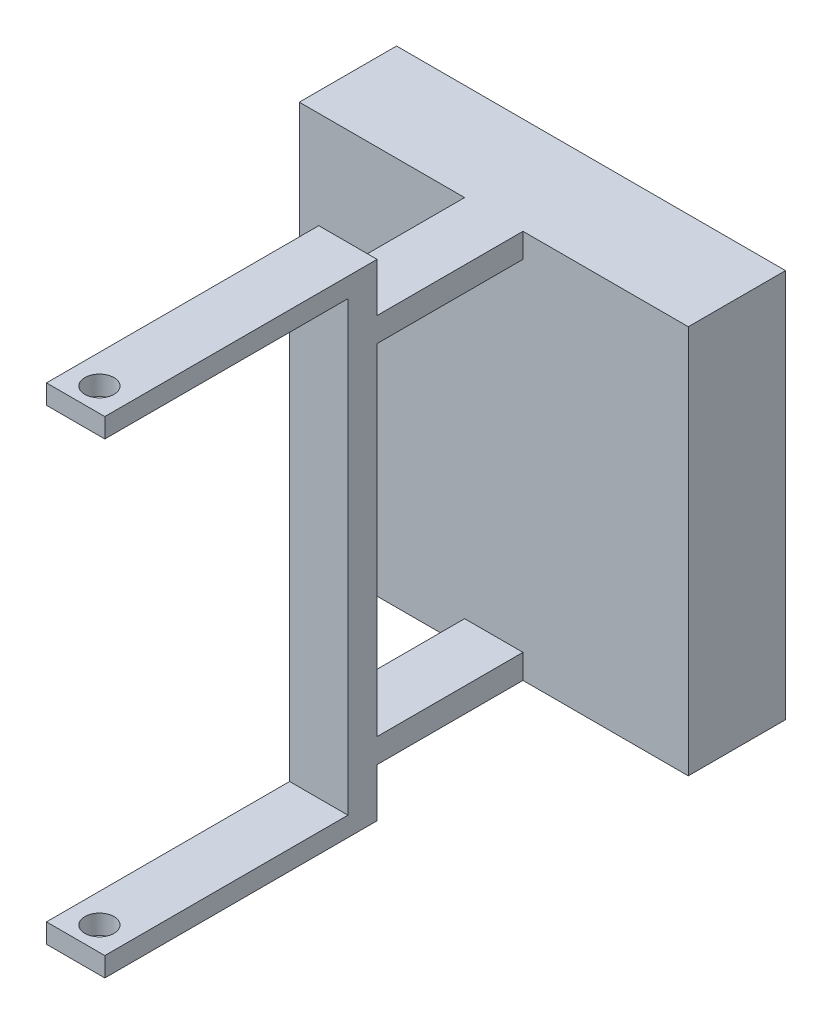
SolidWorks part; units mm, degrees
ref_plane "Front Plane" through (0, 0, 0) normal (0, 0, 1) x (1, 0, 0)
ref_plane "Top Plane" through (0, 0, 0) normal (0, 1, 0) x (1, 0, 0)
ref_plane "Right Plane" through (0, 0, 0) normal (1, 0, 0) x (0, 0, -1)
sketch "Sketch1" plane through (0, 0, 0) normal (0, 0, 1) x (1, 0, 0)
  line L1 (-20, -20) -> (20, -20)
  line L2 (-20, -20) -> (-20, 20)
  line L3 (-20, 20) -> (20, 20)
  line L4 (20, -20) -> (20, 20)
  line L5 (-20, -20) -> (20, 20) construction
  line L6 (-20, 20) -> (20, -20) construction
  point P0 (0, 0)
  dimension "D1" = 40
  dimension "D2" = 40
extrude "Boss-Extrude1" add sketch "Sketch1" along normal blind 10
sketch "Sketch2" plane through (0, 0, 10) normal (0, 0, 1) x (1, 0, 0)
  line L0 (0, -20) -> (3, -20)
  line L1 (-20, -20) -> (20, -20) construction
  line L2 (3, -20) -> (3, -17.5)
  line L3 (3, -17.5) -> (-3, -17.5)
  line L4 (-3, -17.5) -> (-3, -20)
  line L5 (-3, -20) -> (0, -20)
  dimension "D1" = 3
  dimension "D2" = 3
  dimension "D3" = 2.5
extrude "Boss-Extrude2" add sketch "Sketch2" along normal blind 15
mirror "Mirror1" about plane through (0, 0, 0) normal (0, 1, 0) of "Boss-Extrude2"
sketch "Sketch3" plane through (0, 0, 0) normal (0, 0, -1) x (-1, 0, 0)
  line L1 (-6.5, 6.5) -> (6.5, 6.5)
  line L2 (-6.5, 6.5) -> (-6.5, -6.5)
  line L3 (-6.5, -6.5) -> (6.5, -6.5)
  line L4 (6.5, 6.5) -> (6.5, -6.5)
  line L5 (-6.5, 6.5) -> (6.5, -6.5) construction
  line L6 (-6.5, -6.5) -> (6.5, 6.5) construction
  point P0 (0, 0)
  dimension "D1" = 13
  dimension "D2" = 13
ref_plane "Plane4" through (0, 0, 25) normal (0, 0, 1) x (1, 0, 0)
sketch "Sketch6" plane through (0, 0, 25) normal (0, 0, 1) x (1, 0, 0)
  line L1 (-3, 25) -> (3, 25)
  line L2 (-3, 25) -> (-3, -25)
  line L3 (-3, -25) -> (3, -25)
  line L4 (3, 25) -> (3, -25)
  line L5 (-3, 25) -> (3, -25) construction
  line L6 (-3, -25) -> (3, 25) construction
  point P0 (0, 0)
  dimension "D1" = 50
  dimension "D2" = 6
extrude "Boss-Extrude4" add sketch "Sketch6" along normal blind 3
sketch "Sketch7" plane through (0, 0, 28) normal (0, 0, 1) x (1, 0, 0)
  line L0 (3, -25) -> (3, -23)
  line L1 (3, -25) -> (3, 25) construction
  line L2 (3, -23) -> (-3, -23)
  line L3 (-3, 25) -> (-3, -25) construction
  line L4 (-3, -23) -> (-3, -25)
  line L5 (-3, -25) -> (3, -25)
  dimension "D1" = 2
extrude "Boss-Extrude5" add sketch "Sketch7" along normal blind 25
mirror "Mirror2" about plane through (0, 0, 0) normal (0, 1, 0) of "Boss-Extrude5"
sketch "Sketch8" plane through (0, -25, 0) normal (0, -1, 0) x (1, 0, 0)
  circle A0 centre (0, 50.5557) radius 1.5
  dimension "D1" = 3
extrude "Cut-Extrude1" cut sketch "Sketch8" against normal blind 65
sketch "Sketch9" plane through (0, 0, 0) normal (0, 0, -1) x (-1, 0, 0)
  line L0 (-6.5, 6.5) -> (6.5, -6.5) construction
  circle A0 centre (0, 0) radius 10
  dimension "D1" = 20
sketch "Sketch10" plane through (0, 0, 0) normal (0, 0, -1) x (-1, 0, 0)
  line L0 (-6.5, -6.5) -> (6.5, 6.5) construction
  circle A0 centre (0, 0) radius 10
extrude "Boss-Extrude7" add sketch "Sketch10" along normal blind 5
